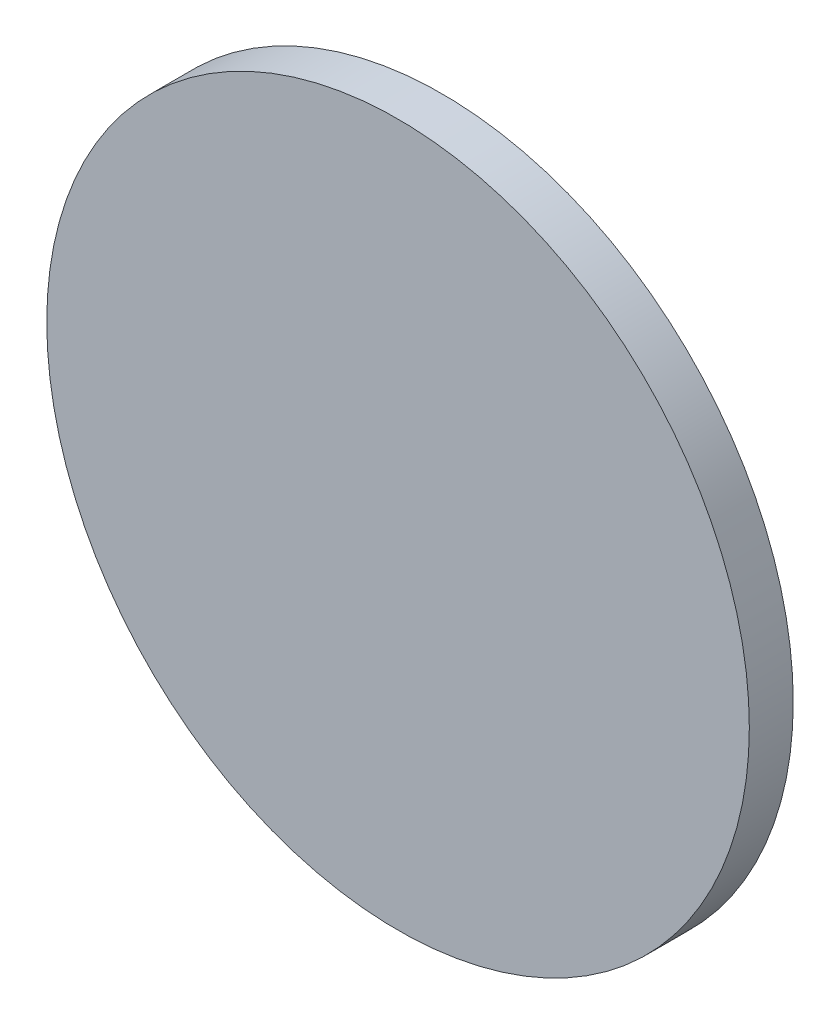
SolidWorks part; units mm, degrees
ref_plane "Front Plane" through (0, 0, 0) normal (0, 0, 1) x (1, 0, 0)
ref_plane "Top Plane" through (0, 0, 0) normal (0, 1, 0) x (1, 0, 0)
ref_plane "Right Plane" through (0, 0, 0) normal (1, 0, 0) x (0, 0, -1)
sketch "Sketch1" plane through (0, 0, 0) normal (0, 0, 1) x (1, 0, 0)
  circle A0 centre (0, 0) radius 24
  dimension "addendumDiameter " = 48
extrude "Boss-Extrude1" add sketch "Sketch1" along normal blind 3
sketch "Sketch2" plane through (0, 0, 3) normal (0, 0, 1) x (1, 0, 0)
  line L0 (0, 0) -> (0, 31.2008) construction
  line L1 (0, 0) -> (-3.262, 31.0361) construction
  line L2 (-1.1632, 22.3381) -> (-2.3349, 22.215) construction
  circle A0 centre (0, 0) radius 20.625 construction
  circle A1 centre (0, 0) radius 21.1431 construction
  circle A2 centre (0, 0) radius 22.5 construction
  arc A3 (-2.0653, 23.911) -> (-0.5947, 20.6164) centre (-9.3817, 18.6697) cw
  circle A6 centre (0, 0) radius 24 construction
  arc A7 (2.0653, 23.911) -> (0.5947, 20.6164) centre (9.3817, 18.6697) ccw
  point P17 (2.1942, 23.8995)
  point P18 (-1.1645, 22.3498)
  point P19 (-9.8171, 24.6444)
  point P20 (-0.5947, 20.6164)
  dimension "dedendumCircle" = 41.25
  dimension "baseDiameter" = 42.2862
  dimension "pitchDiameter" = 45
  dimension "D2" = 9
  dimension "D1" = 6
  dimension "D3" = 1.1781
equation "\"module\"= 1.5"
equation "\"teeth\"= 30"
equation "\"pressureAngle\"= 20deg"
equation "\"gearThickness\"= 3"
equation "\"addendumFactor\"= 1"
equation "\"dedendumFactor\"= 1.25"
equation "\"pitch\"= 1/\"module\""
equation "\"pitchDiameter\"= \"teeth\" / \"pitch\""
equation "\"addendum\"= \"addendumFactor\" / \"pitch\""
equation "\"dedendum\"= \"dedendumFactor\" / \"pitch\""
equation "\"addendumDiameter @Sketch1\"= \"pitchDiameter\" + 2 * \"addendum\""
equation "\"D1@Boss-Extrude1\"= \"gearThickness\""
equation "\"dedendumCircle@Sketch2\" = \"pitchDiameter\" - 2 * \"dedendum\""
equation "\"baseDiameter@Sketch2\"=\"pitchDiameter\" * cos ( \"pressureAngle\" )"
equation "\"pitchDiameter@Sketch2\"=\"pitchDiameter\""
equation "\"D1@Sketch2\"=180/\"teeth\""
equation "\"D2@Sketch2\"=\"pitchDiameter\"/5"
equation "\"D3@Sketch2\"=PI / 2 / \"pitch\" / 2"
